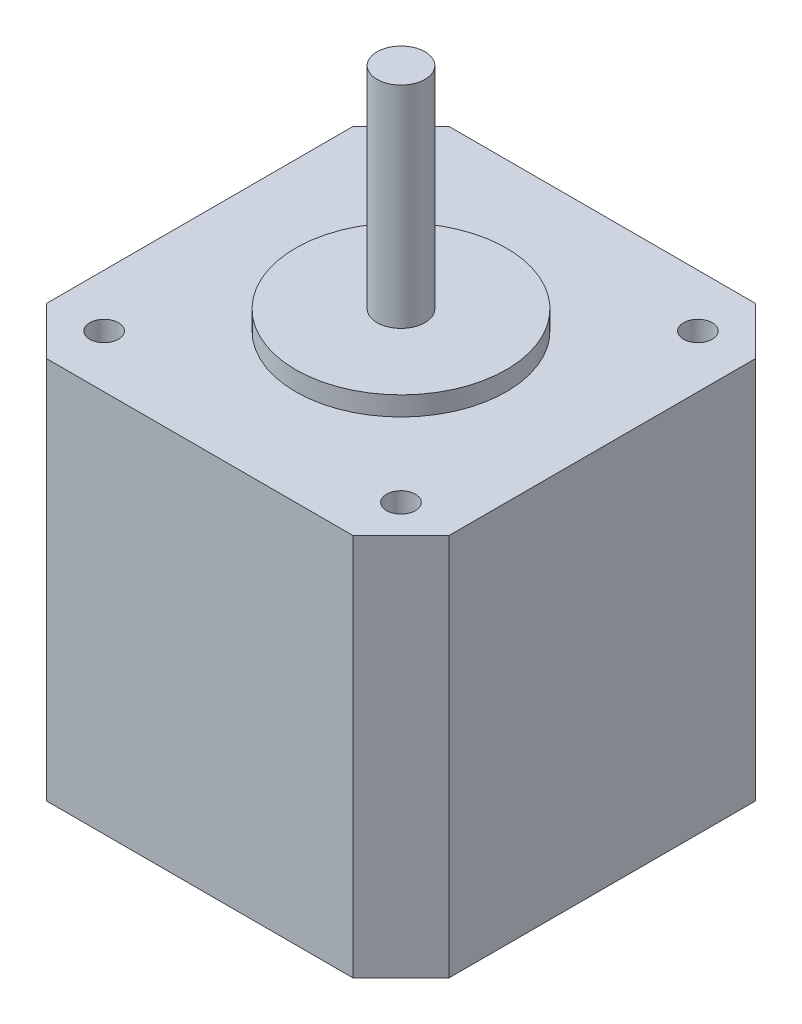
SolidWorks part; units mm, degrees
ref_plane "前视基准面" through (0, 0, 0) normal (0, 0, 1) x (1, 0, 0)
ref_plane "上视基准面" through (0, 0, 0) normal (0, 1, 0) x (1, 0, 0)
ref_plane "右视基准面" through (0, 0, 0) normal (1, 0, 0) x (0, 0, -1)
sketch "草图1" plane through (0, 0, 0) normal (0, 1, 0) x (1, 0, 0)
  line L1 (-21, 21) -> (21, 21)
  line L2 (-21, 21) -> (-21, -21)
  line L3 (-21, -21) -> (21, -21)
  line L4 (21, 21) -> (21, -21)
  line L5 (0, -21) -> (0, 21) construction
  line L6 (-21, 0) -> (21, 0) construction
  point P0 (0, 0)
  dimension "D1" = 42
extrude "凸台-拉伸1" add sketch "草图1" along normal blind 40
sketch "草图2" plane through (0, 40, 0) normal (0, 1, 0) x (1, 0, 0)
  circle A0 centre (0, 0) radius 11
  dimension "D1" = 22
extrude "凸台-拉伸2" add sketch "草图2" along normal blind 2
sketch "草图3" plane through (0, 42, 0) normal (0, 1, 0) x (1, 0, 0)
  circle A0 centre (0, 0) radius 2.5
  dimension "D1" = 5
extrude "凸台-拉伸3" add sketch "草图3" along normal blind 22
sketch "草图4" plane through (0, 40, 0) normal (0, 1, 0) x (1, 0, 0)
  line L1 (-15.5, 15.5) -> (15.5, 15.5) construction
  line L2 (-15.5, 15.5) -> (-15.5, -15.5) construction
  line L3 (-15.5, -15.5) -> (15.5, -15.5) construction
  line L4 (15.5, 15.5) -> (15.5, -15.5) construction
  line L5 (0, -15.5) -> (0, 15.5) construction
  line L6 (-15.5, 0) -> (15.5, 0) construction
  circle A0 centre (-15.5, 15.5) radius 1.5
  circle A1 centre (15.5, 15.5) radius 1.5
  circle A2 centre (15.5, -15.5) radius 1.5
  circle A3 centre (-15.5, -15.5) radius 1.5
  point P0 (0, 0)
  dimension "D2" = 3
  dimension "D1" = 31
extrude "切除-拉伸1" cut sketch "草图4" against normal blind 4.5
chamfer "倒角1" distance 5 angle 45 4 edges at (-21, 20, 21) (21, 20, 21) (21, 20, -21) (-21, 20, -21)
sketch "草图5" plane through (-21, 0, 0) normal (-1, 0, 0) x (0, 0, 1)
  line L1 (-8.211, 2.1161) -> (8.211, 2.1161)
  line L2 (-8.211, 2.1161) -> (-8.211, 0)
  line L4 (8.211, 2.1161) -> (8.211, 0)
  line L5 (0, 0) -> (0, 2.1161) construction
  line L6 (-8.211, 0) -> (8.211, 0) construction
  line L7 (-8.211, 0) -> (8.211, 0)
  point P0 (0, 0)
extrude "凸台-拉伸4" add sketch "草图5" along normal blind 7
